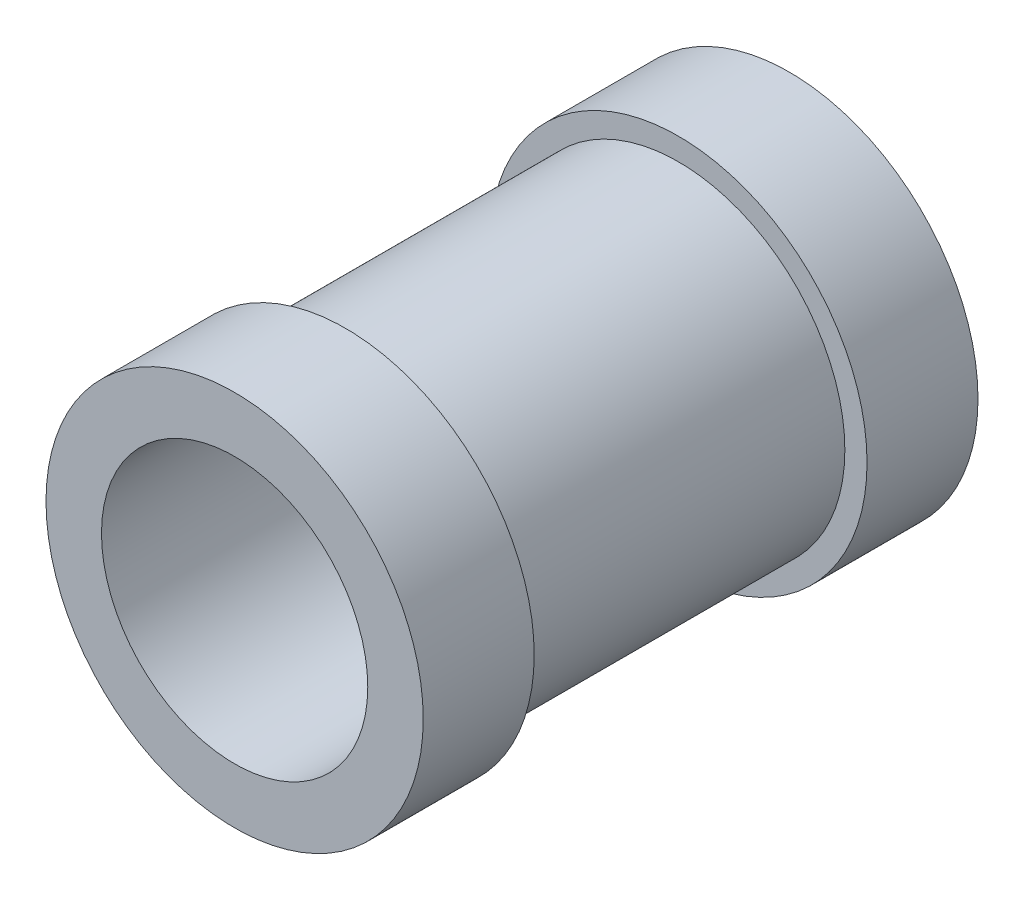
SolidWorks part; units mm, degrees
ref_plane "Front Plane" through (0, 0, 0) normal (0, 0, 1) x (1, 0, 0)
ref_plane "Top Plane" through (0, 0, 0) normal (0, 1, 0) x (1, 0, 0)
ref_plane "Right Plane" through (0, 0, 0) normal (1, 0, 0) x (0, 0, -1)
sketch "Sketch1" plane through (0, 0, 0) normal (0, 0, 1) x (1, 0, 0)
  circle A1 centre (15, 15) radius 1.2
  circle A2 centre (15, 15) radius 1.5
extrude "Boss-Extrude1" add sketch "Sketch1" along normal blind 5
sketch "Sketch2" plane through (0, 0, 5) normal (0, 0, 1) x (1, 0, 0)
  circle A0 centre (15, 15) radius 1.2 construction
  circle A1 centre (15, 15) radius 1.2
  circle A2 centre (15, 15) radius 1.7
extrude "Boss-Extrude2" add sketch "Sketch2" against normal blind 1
sketch "Sketch3" plane through (0, 0, 0) normal (0, 0, -1) x (-1, 0, 0)
  circle A0 centre (-15, 15) radius 1.2 construction
  circle A1 centre (-15, 15) radius 1.7
  circle A2 centre (-15, 15) radius 1.7
  circle A3 centre (-15, 15) radius 1.2
  dimension "D1" = 0
extrude "Boss-Extrude3" add sketch "Sketch3" against normal blind 1
